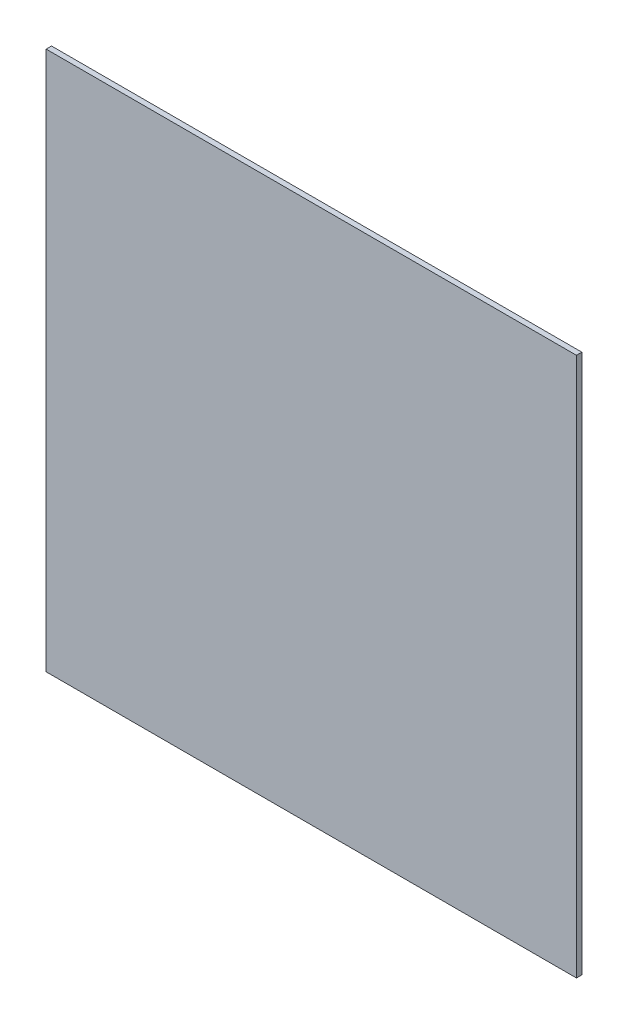
SolidWorks part; units mm, degrees
material "Стекло"
ref_plane "Спереди" through (0, 0, 0) normal (0, 0, 1) x (1, 0, 0)
ref_plane "Сверху" through (0, 0, 0) normal (0, 1, 0) x (1, 0, 0)
ref_plane "Справа" through (0, 0, 0) normal (1, 0, 0) x (0, 0, -1)
sketch "Эскиз1" plane through (0, 0, 0) normal (0, 0, 1) x (1, 0, 0)
  line L1 (0, 0) -> (590, 0)
  line L2 (0, 0) -> (0, 600)
  line L3 (0, 600) -> (590, 600)
  line L4 (590, 0) -> (590, 600)
  dimension "D1" = 590
  dimension "D2" = 600
extrude "Бобышка-Вытянуть1" add sketch "Эскиз1" along normal blind 6
